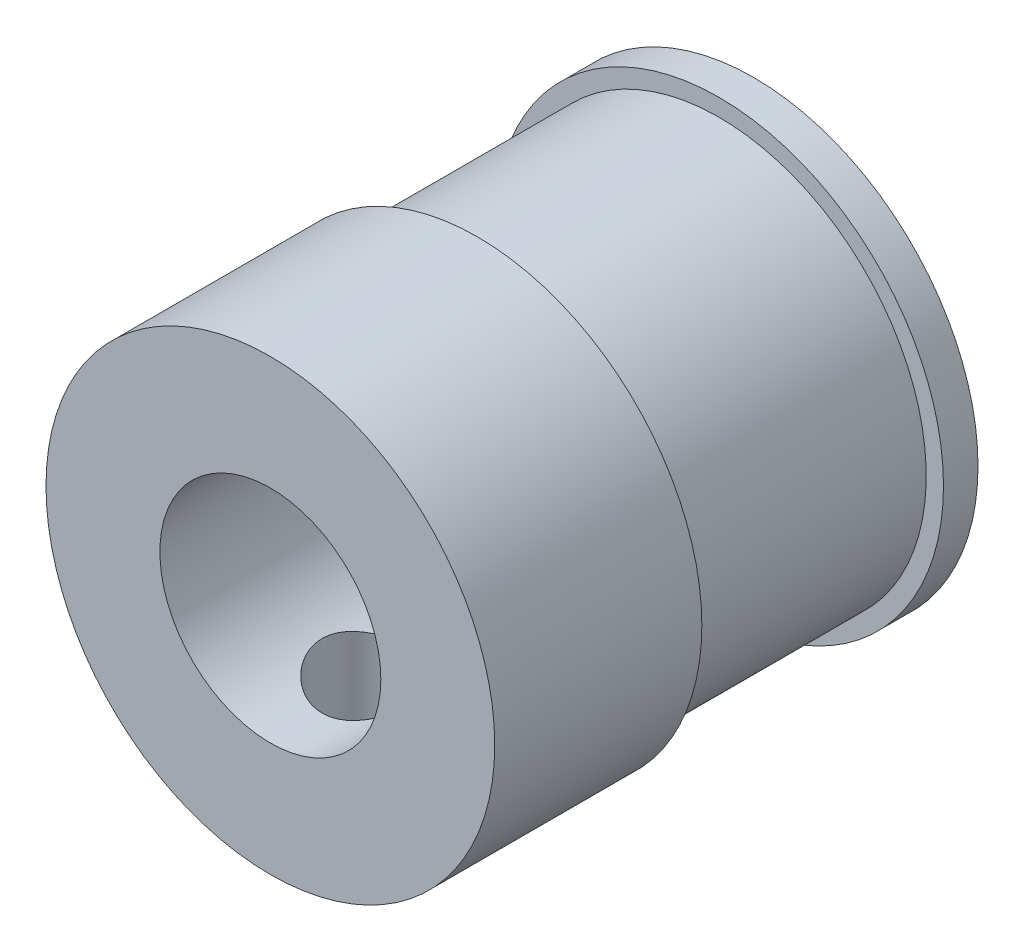
SolidWorks part; units mm, degrees
ref_plane "Front Plane" through (0, 0, 0) normal (0, 0, 1) x (1, 0, 0)
ref_plane "Top Plane" through (0, 0, 0) normal (0, 1, 0) x (1, 0, 0)
ref_plane "Right Plane" through (0, 0, 0) normal (1, 0, 0) x (0, 0, -1)
sketch "Sketch1" plane through (0, 0, 0) normal (0, 0, 1) x (1, 0, 0)
  circle A0 centre (0, 0) radius 6.5
  dimension "D1" = 13
extrude "Boss-Extrude1" add sketch "Sketch1" along normal blind 14
sketch "Sketch2" plane through (0, 0, 14) normal (0, 0, 1) x (1, 0, 0)
  circle A0 centre (0, 0) radius 3.2
  dimension "D1" = 6.4
extrude "Cut-Extrude1" cut sketch "Sketch2" against normal through all
ref_plane "Plane1" through (0, 0, 1) normal (0, 0, -1) x (-1, 0, 0)
sketch "Sketch3" plane through (0, 0, 1) normal (0, 0, -1) x (-1, 0, 0)
  circle A0 centre (0, 0) radius 6
  circle A1 centre (0, 0) radius 6.5 construction
  circle A2 centre (0, 0) radius 6.5
  dimension "D1" = 0.5
extrude "Cut-Extrude2" cut sketch "Sketch3" against normal blind 7
sketch "Sketch4" plane through (0, 0, 0) normal (0, 1, 0) x (1, 0, 0)
  line L0 (0, -14) -> (0, -11) construction
  line L1 (-6.5, -14) -> (6.5, -14) construction
  circle A0 centre (0, -11) radius 1.5
  dimension "D1" = 3
  dimension "D2" = 3
extrude "Cut-Extrude3" cut sketch "Sketch4" against normal blind 7
